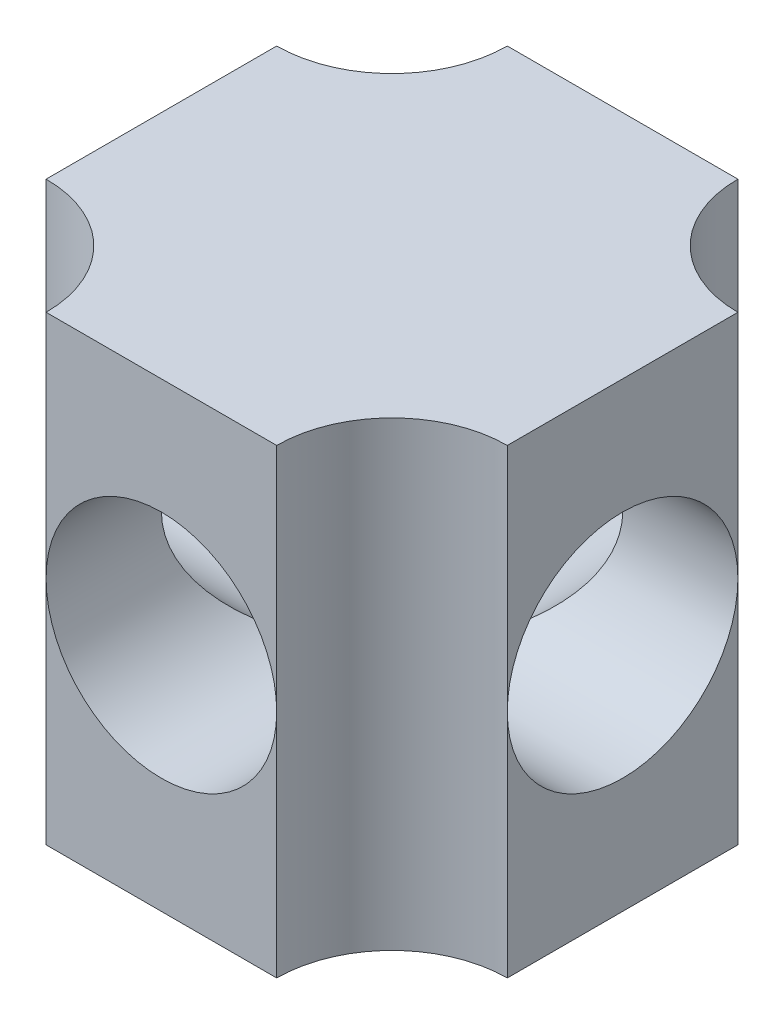
SolidWorks part; units mm, degrees
ref_plane "Front Plane" through (0, 0, 0) normal (0, 0, 1) x (1, 0, 0)
ref_plane "Top Plane" through (0, 0, 0) normal (0, 1, 0) x (1, 0, 0)
ref_plane "Right Plane" through (0, 0, 0) normal (1, 0, 0) x (0, 0, -1)
other "Center of Mass"
sketch "Sketch1" plane through (0, 0, 0) normal (0, 1, 0) x (1, 0, 0)
  line L1 (-50, -50) -> (50, -50)
  line L2 (-50, -50) -> (-50, 50)
  line L3 (-50, 50) -> (50, 50)
  line L4 (50, -50) -> (50, 50)
  line L5 (-50, -50) -> (50, 50) construction
  line L6 (-50, 50) -> (50, -50) construction
  point P0 (0, 0)
  dimension "D1" = 100
  dimension "D2" = 100
extrude "Boss-Extrude1" add sketch "Sketch1" along normal blind 100
sketch "Sketch3" plane through (0, 0, 50) normal (0, 0, 1) x (1, 0, 0)
  line L0 (0, 100) -> (0, 0) construction
  line L1 (-50, 100) -> (50, 100) construction
  line L2 (-50, 50) -> (50, 50) construction
  line L3 (-50, 100) -> (-50, 0) construction
  line L4 (50, 100) -> (50, 0) construction
  circle A0 centre (0, 50) radius 25
  point P11 (0, 50)
  dimension "D1" = 50
extrude "Cut-Extrude3" cut sketch "Sketch3" against normal through all
sketch "Sketch5" plane through (-50, 0, 0) normal (-1, 0, 0) x (0, 0, 1)
  line L0 (0, 100) -> (0, 0) construction
  line L2 (-50, 50) -> (50, 50) construction
  line L5 (-50, 100) -> (50, 100) construction
  line L6 (-50, 0) -> (50, 0) construction
  circle A0 centre (0, 50) radius 25
  point P11 (0, 50)
  dimension "D1" = 50
extrude "Cut-Extrude4" cut sketch "Sketch5" against normal through all
sketch "Sketch9" plane through (0, 100, 0) normal (0, 1, 0) x (0, 0, 1)
  line L0 (-50, -26.0911) -> (-50, -73.9089) construction
  line L2 (-78.3786, -50) -> (21.6214, -50) construction
  circle A0 centre (-50, -50) radius 25
  point P11 (-50, -50)
  dimension "D1" = 50
extrude "Cut-Extrude5" cut sketch "Sketch9" against normal blind 100
pattern_linear "LPattern1" count 2 spacing 100 along (1, 0, 0) count 2 spacing 100 along (0, 0, 1) of "Cut-Extrude5"
ref_point "Center"
equation "\"D1@Boss-Extrude1\"=\"D1@Sketch1\""
equation "\"D1@Cut-Extrude5\"=\"D1@Sketch1\""
